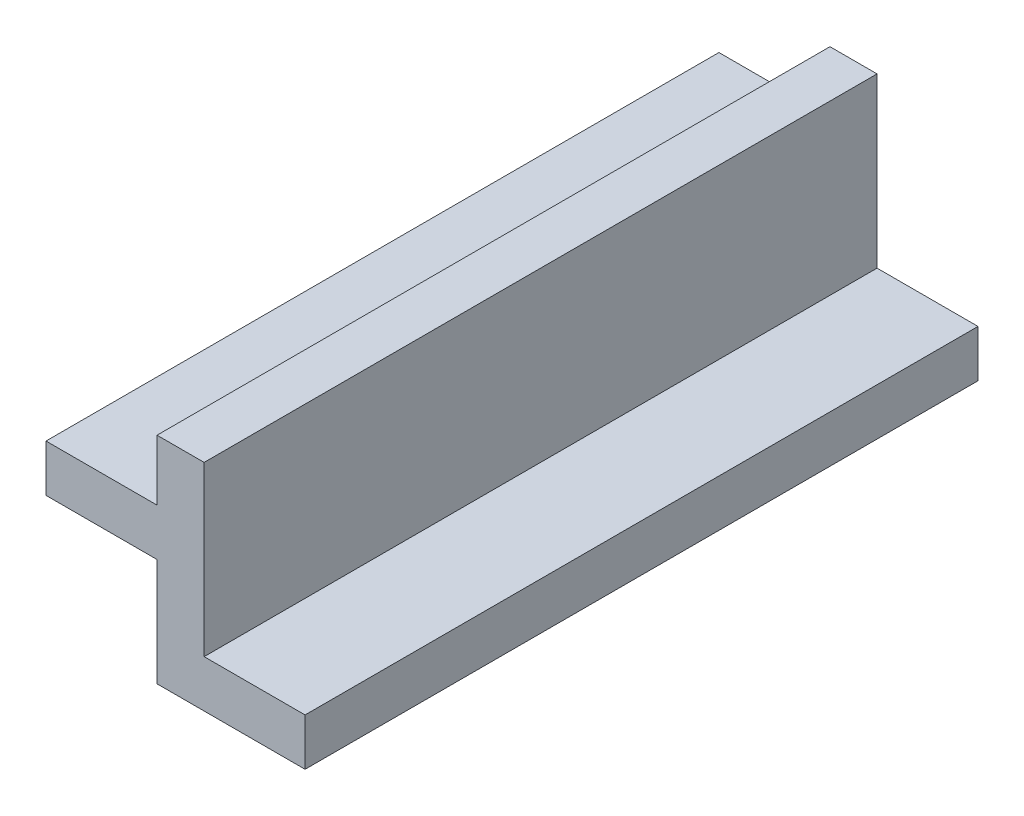
SolidWorks part; units mm, degrees
ref_plane "Спереди" through (0, 0, 0) normal (0, 0, 1) x (1, 0, 0)
ref_plane "Сверху" through (0, 0, 0) normal (0, 1, 0) x (1, 0, 0)
ref_plane "Справа" through (0, 0, 0) normal (1, 0, 0) x (0, 0, -1)
sketch "Эскиз1" plane through (0, 0, 0) normal (0, 0, 1) x (1, 0, 0)
  line L1 (-3.5, -16) -> (3.5, -16)
  line L2 (-3.5, -16) -> (-3.5, 16)
  line L3 (-3.5, 16) -> (3.5, 16)
  line L4 (3.5, -16) -> (3.5, 16)
  line L5 (-3.5, -16) -> (3.5, 16) construction
  line L6 (-3.5, 16) -> (3.5, -16) construction
  line L7 (3.5, -16) -> (18.5, -16)
  line L8 (3.5, -16) -> (3.5, -9)
  line L9 (3.5, -9) -> (18.5, -9)
  line L10 (18.5, -16) -> (18.5, -9)
  line L11 (0, 0) -> (-20, 0)
  line L12 (0, 0) -> (0, 7)
  line L13 (0, 7) -> (-20, 7)
  line L14 (-20, 0) -> (-20, 7)
  point P0 (0, 0)
  dimension "D1" = 7
  dimension "D2" = 32
  dimension "D3" = 15
  dimension "D4" = 20
extrude "Бобышка-Вытянуть1" add sketch "Эскиз1" along normal blind 100 contours L14 L11 L2 L13 | L12 L13 L2 L11 | L13 L12 L11 L2 L1 L4 L3 | L7 L10 L9 L4
